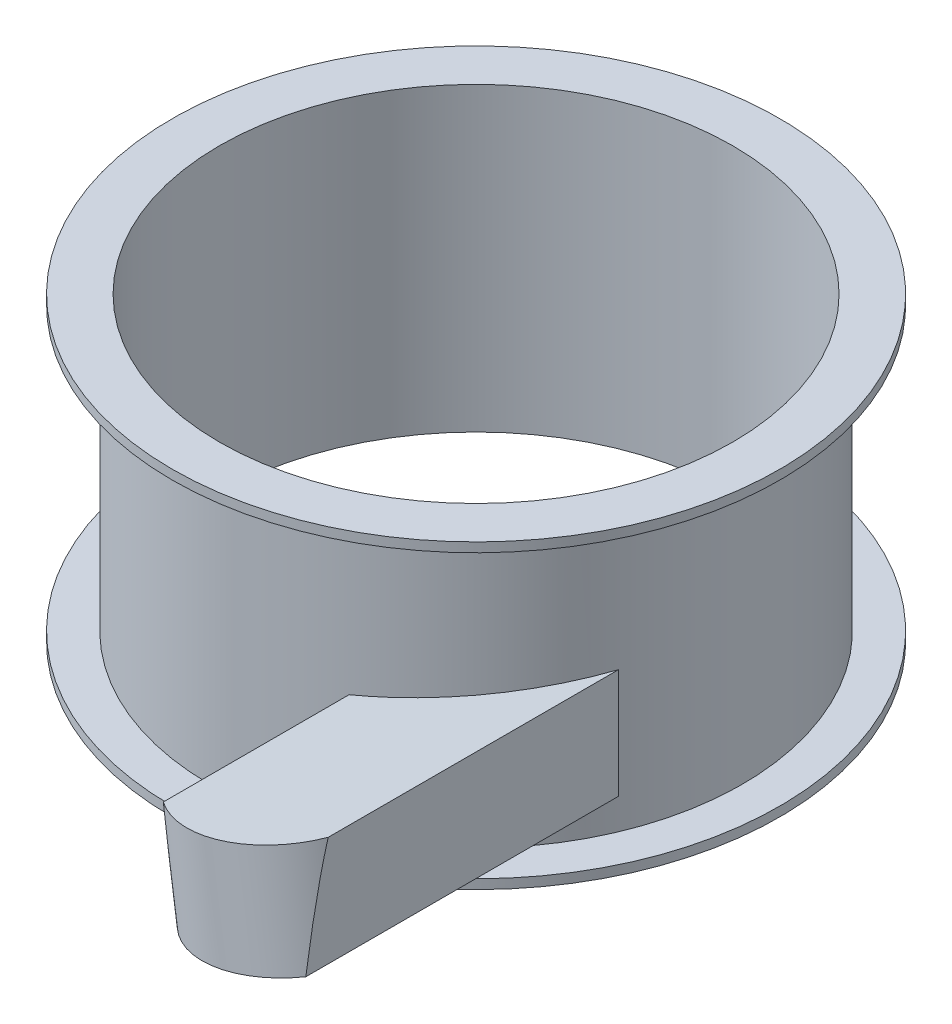
SolidWorks part; units mm, degrees
ref_plane "Front Plane" through (0, 0, 0) normal (0, 0, 1) x (1, 0, 0)
ref_plane "Top Plane" through (0, 0, 0) normal (0, 1, 0) x (1, 0, 0)
ref_plane "Right Plane" through (0, 0, 0) normal (1, 0, 0) x (0, 0, -1)
sketch "Sketch1" plane through (0, 0, 0) normal (0, 0, 1) x (1, 0, 0)
  line L0 (0, 0) -> (-20, 0)
  line L1 (0, 0) -> (0, 150)
  line L2 (-20, 0) -> (-20, -5)
  line L3 (-20, -5) -> (5, -5)
  line L4 (5, -5) -> (141.4, -5)
  line L7 (141.4, 150) -> (141.4, -5)
  line L8 (0, 150) -> (-20, 150)
  line L9 (-20, 150) -> (-20, 155)
  line L10 (-20, 155) -> (141.4, 155)
  line L11 (141.4, 155) -> (141.4, 150)
  point P7 (-7.5, -5)
  dimension "D1" = 20
  dimension "D2" = 150
  dimension "D3" = 136.4
  dimension "D4" = 5
sketch "Sketch2" plane through (0, 0, 0) normal (0, 0, 1) x (1, 0, 0)
revolve "Revolve1" add sketch "Sketch1" angle 360 about L7
ref_plane "Plane1" through (0, 0, 140) normal (0, 0, 1) x (1, 0, 0)
sketch "Sketch3" plane through (0, 0, 140) normal (0, 0, 1) x (1, 0, 0)
  line L1 (271.7878, 74.6313) -> (201.7878, 64.6851)
  line L2 (271.7878, 16.3749) -> (201.7878, 6.4287)
  line L3 (201.7878, 6.4287) -> (201.7878, 64.6851)
  line L5 (271.7878, 74.6313) -> (271.7878, 16.3749)
  point P1 (268.5695, 68.4741)
  point P2 (198.4723, 11.8448)
  point P3 (266.675, 77.9467)
  point P7 (274.7267, 30.5838)
  point P8 (0, 0)
  point P9 (0, 0)
  point P10 (198.946, 6.4287)
  point P11 (267.6222, 16.3749)
  point P12 (201.7878, 64.6851)
  point P13 (0, 0)
  dimension "D1" = 70
extrude "Boss-Extrude2" add sketch "Sketch3" along normal mid plane 202
ref_plane "Plane2" through (4.5047, -31.7035, 0) normal (0.1407, -0.9901, 0) x (-0.9901, -0.1407, 0)
sketch "Sketch4" plane through (4.5047, -31.7035, 0) normal (0.1407, -0.9901, 0) x (-0.9901, -0.1407, 0)
  line L7 (-283.0967, -198.9828) -> (-292.5245, -243.5493)
  line L8 (-292.5245, -243.5493) -> (-246.6966, -274.0421)
  line L9 (-246.6966, -274.0421) -> (-190.71, -274.0421)
  line L10 (-190.71, -274.0421) -> (-190.71, -198.9828)
  arc A1 (-283.0967, -198.9828) -> (-190.71, -198.9828) centre (-236.9033, -188.3433) ccw
extrude "Cut-Extrude3" cut sketch "Sketch4" against normal through all both and the other way through all
sketch "Sketch5" plane through (4.5047, -31.7035, 0) normal (0.1407, -0.9901, 0) x (-0.9901, -0.1407, 0)
  circle A0 centre (-236.587, -195.245) radius 28.1465
extrude "Cut-Extrude4" cut sketch "Sketch5" against normal blind 64 and the other way through all
sketch "Sketch6" plane through (0, 0, 140) normal (0, 0, 1) x (1, 0, 0)
  line L0 (206.7878, 60.4224) -> (206.7878, 12.1894)
  line L1 (206.7878, 12.1894) -> (266.7878, 20.7147)
  line L2 (266.7878, 20.7147) -> (266.7878, 68.8522)
  line L3 (266.7878, 68.8522) -> (206.7878, 60.4224)
extrude "Cut-Extrude7" cut sketch "Sketch6" against normal blind 113 and the other way blind 36
sketch "Sketch8" plane through (0, 0, 0) normal (0, 1, 0) x (1, 0, 0)
  circle A0 centre (141.4, 0) radius 136.4
extrude "Cut-Extrude8" cut sketch "Sketch8" against normal through all both and the other way through all
